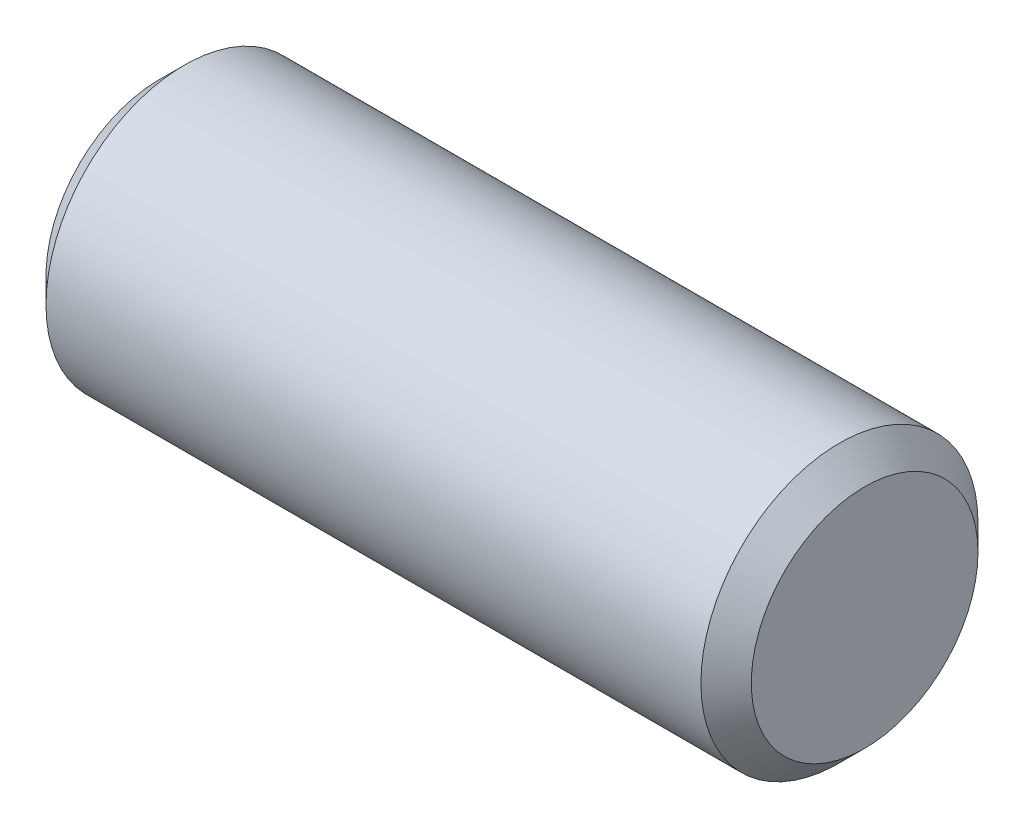
SolidWorks part; units mm, degrees
material "Простая углеродистая сталь"
ref_plane "Спереди" through (0, 0, 0) normal (0, 0, 1) x (1, 0, 0)
ref_plane "Сверху" through (0, 0, 0) normal (0, 1, 0) x (1, 0, 0)
ref_plane "Справа" through (0, 0, 0) normal (1, 0, 0) x (0, 0, -1)
other "Табл. исп."
sketch "Эскиз1" plane through (0, 0, 0) normal (0, 0, 1) x (1, 0, 0)
  line L0 (0, 0) -> (-91.9027, 0) construction
  line L1 (0, 0) -> (0, 9)
  line L3 (-2, 11) -> (-54, 11)
  line L4 (-56, 9) -> (-56, 0)
  line L5 (-56, 0) -> (0, 0)
  line L6 (0, 9) -> (-2, 11)
  line L7 (-54, 11) -> (-56, 9)
  point P4 (0, 11)
  point P9 (-56, 11)
  dimension "D1" = 22
  dimension "D5" = 56
  dimension "D6" = 2
  dimension "D7" = 45
  dimension "D8" = 2
  dimension "D9" = 45
revolve "Повернуть1" add sketch "Эскиз1" angle 360 about L0
